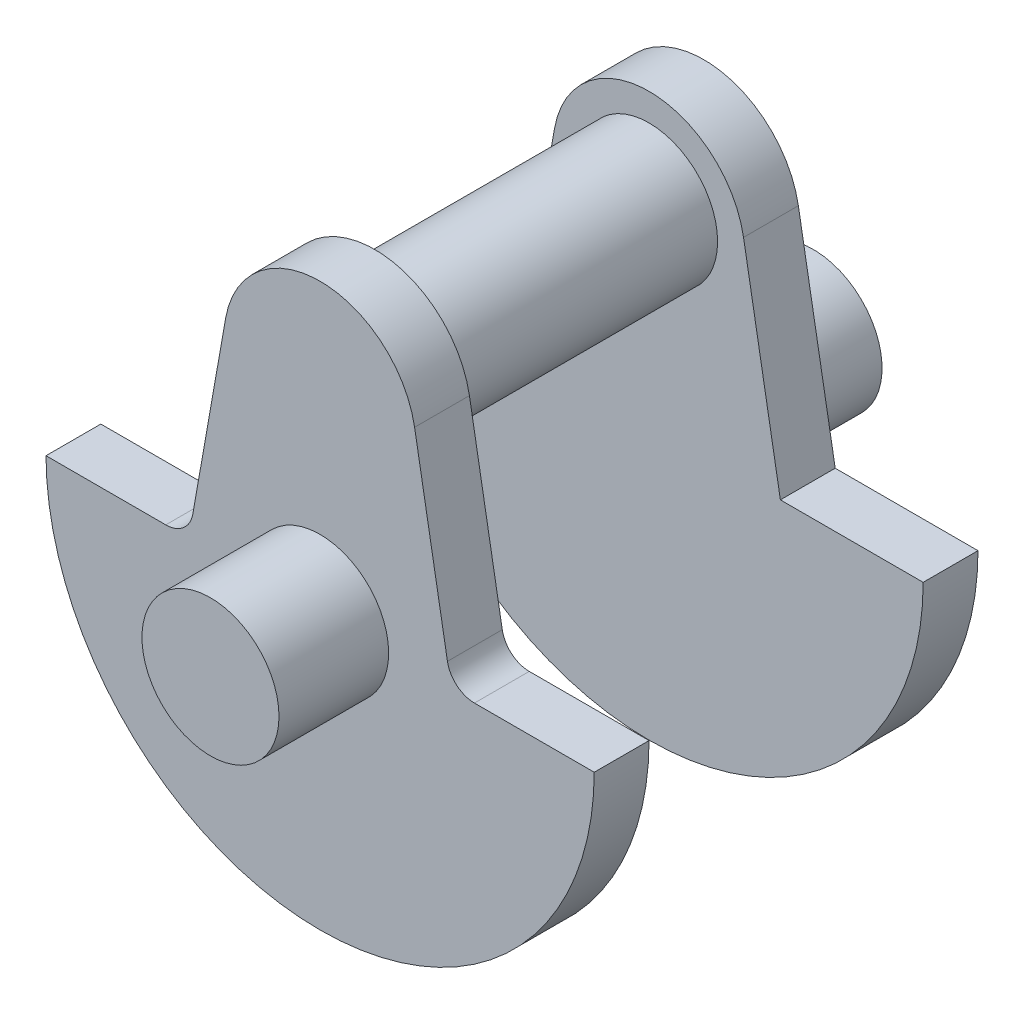
SolidWorks part; units mm, degrees
ref_plane "Front Plane" through (0, 0, 0) normal (0, 0, 1) x (1, 0, 0)
ref_plane "Top Plane" through (0, 0, 0) normal (0, 1, 0) x (1, 0, 0)
ref_plane "Right Plane" through (0, 0, 0) normal (1, 0, 0) x (0, 0, -1)
sketch "Sketch2" plane through (0, 0, 0) normal (0, 0, 1) x (1, 0, 0)
  circle A0 centre (0, 0) radius 12.5
  dimension "D1" = 25
extrude "Boss-Extrude1" add sketch "Sketch2" along normal blind 20
sketch "Sketch3" plane through (0, 0, 0) normal (0, 0, 1) x (1, 0, 0)
  line L0 (-50, -0.0681) -> (-23.9534, -0.0681)
  line L1 (-17.2341, 38.0388) -> (-23.9534, -0.0681)
  line L2 (0, 50.218) -> (0, -22.3114) construction
  line L3 (17.2341, 38.0388) -> (23.9534, -0.0681)
  line L4 (23.9534, -0.0681) -> (50, -0.0681)
  arc A0 (-50, -0.0681) -> (50, -0.0681) centre (0, 0) ccw
  arc A1 (17.2341, 38.0388) -> (-17.2341, 38.0388) centre (0, 35) ccw
  point P3 (-24.3395, 0)
  dimension "D1" = 100
  dimension "D2" = 35
  dimension "D3" = 35
  dimension "D4" = 10
extrude "Boss-Extrude2" add sketch "Sketch3" against normal blind 10
fillet "Fillet1" radius 5 2 edges at (-23.9534, -0.0681, -5) (23.9534, -0.0681, -5)
sketch "Sketch4" plane through (0, 0, -10) normal (0, 0, -1) x (-1, 0, 0)
  circle A0 centre (0, 35) radius 12.5
  dimension "D1" = 25
extrude "Boss-Extrude3" add sketch "Sketch4" along normal blind 50
ref_plane "Plane1" through (0, 0, -35) normal (0, 0, -1) x (-1, 0, 0)
mirror "Mirror1" about plane through (0, 0, -35) normal (0, 0, -1) of "Boss-Extrude1", "Boss-Extrude2"
sketch "Sketch5" plane through (0, 0, -70) normal (0, 0, -1) x (-1, 0, 0)
  circle A0 centre (0, 0) radius 12.5
extrude "Boss-Extrude4" add sketch "Sketch5" along normal blind 20
